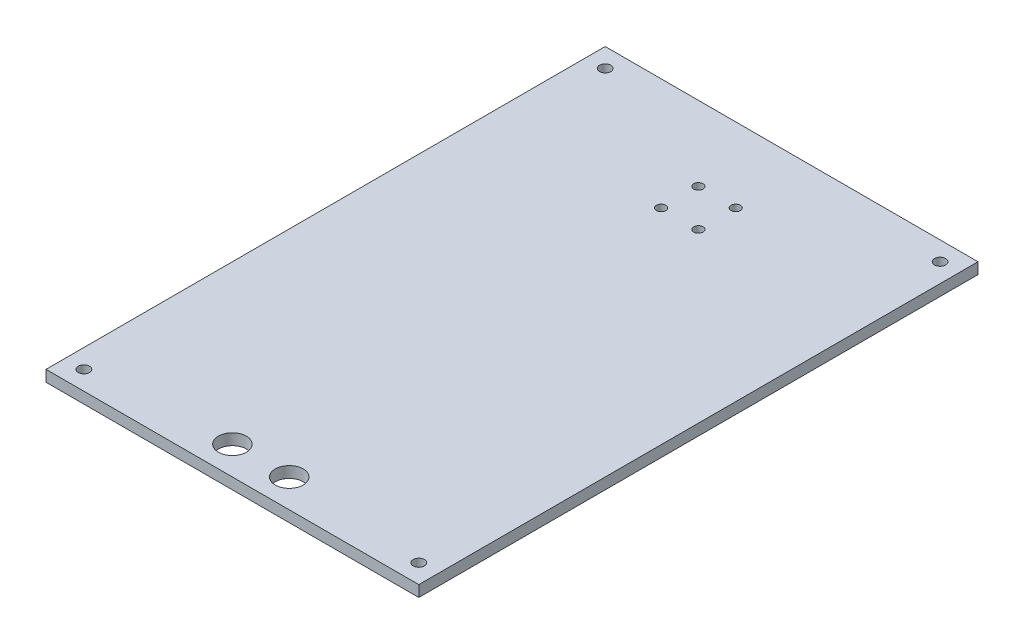
SolidWorks part; units mm, degrees
ref_plane "Front Plane" through (0, 0, 0) normal (0, 0, 1) x (1, 0, 0)
ref_plane "Top Plane" through (0, 0, 0) normal (0, 1, 0) x (1, 0, 0)
ref_plane "Right Plane" through (0, 0, 0) normal (1, 0, 0) x (0, 0, -1)
sketch "Sketch1" plane through (0, 0, 0) normal (0, 1, 0) x (1, 0, 0)
  line L1 (-50, -75) -> (50, -75)
  line L2 (-50, -75) -> (-50, 75)
  line L3 (-50, 75) -> (50, 75)
  line L4 (50, -75) -> (50, 75)
  line L5 (-50, -75) -> (50, 75) construction
  line L6 (-50, 75) -> (50, -75) construction
  point P0 (0, 0)
  dimension "D1" = 150
  dimension "D2" = 100
extrude "Boss-Extrude1" add sketch "Sketch1" along normal blind 3
sketch "Sketch2" plane through (0, 3, 0) normal (0, 1, 0) x (1, 0, 0)
  line L0 (0, 75) -> (0, -75) construction
  line L1 (50, 75) -> (-50, 75) construction
  line L2 (-50, -75) -> (50, -75) construction
  line L3 (-50, 75) -> (-50, -75) construction
  line L4 (50, -75) -> (50, 75) construction
  circle A0 centre (-7.62, -67.38) radius 3.75
  circle A1 centre (7.62, -67.38) radius 3.75
  circle A2 centre (-44.92, 69.92) radius 1.5
  circle A3 centre (44.92, 69.92) radius 1.5
  circle A4 centre (-44.92, -69.92) radius 1.5
  circle A5 centre (44.92, -69.92) radius 1.5
  circle A6 centre (-5, 55) radius 1.25
  circle A7 centre (5, 55) radius 1.25
  circle A8 centre (-5, 45) radius 1.25
  circle A9 centre (5, 45) radius 1.25
  dimension "D1" = 7.5
  dimension "D2" = 7.5
  dimension "D3" = 7.62
  dimension "D4" = 7.62
  dimension "D5" = 7.62
  dimension "D6" = 7.62
  dimension "D7" = 5.08
  dimension "D8" = 5.08
  dimension "D9" = 5.08
  dimension "D10" = 5.08
  dimension "D11" = 5.08
  dimension "D12" = 5.08
  dimension "D13" = 5.08
  dimension "D14" = 5.08
  dimension "D15" = 5
  dimension "D16" = 5
  dimension "D17" = 5
  dimension "D18" = 5
  dimension "D19" = 20
  dimension "D20" = 10
  dimension "D21" = 20
  dimension "D22" = 10
  dimension "D23" = 3
  dimension "D24" = 3
  dimension "D25" = 3
  dimension "D26" = 3
extrude "Cut-Extrude1" cut sketch "Sketch2" against normal blind 3
